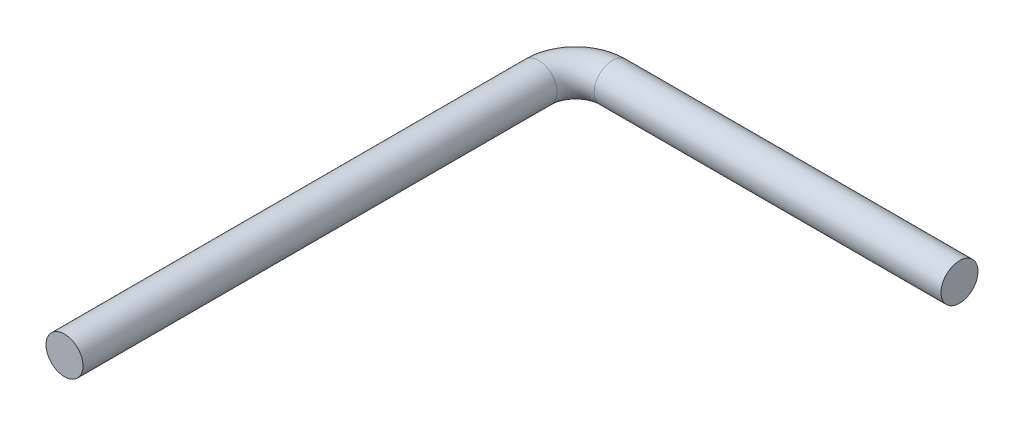
SolidWorks part; units mm, degrees
material "PLA"
ref_plane "Front Plane" through (0, 0, 0) normal (0, 0, 1) x (1, 0, 0)
ref_plane "Top Plane" through (0, 0, 0) normal (0, 1, 0) x (1, 0, 0)
ref_plane "Right Plane" through (0, 0, 0) normal (1, 0, 0) x (0, 0, -1)
sketch "Sketch1" plane through (0, 0, 0) normal (0, 1, 0) x (1, 0, 0)
  line L0 (7.8913, 18.9949) -> (-15.9212, 18.9949)
  line L1 (-18.4612, 16.4549) -> (-18.4612, -16.0876)
  arc A0 (-15.9212, 18.9949) -> (-18.4612, 16.4549) centre (-15.9212, 16.4549) ccw
  point P5 (-18.4612, 18.9949)
  dimension "D3" = 2.54
  dimension "D1" = 23.8125
  dimension "D2" = 32.5425
sketch "Sketch3" plane through (0, 0, 0) normal (1, 0, 0) x (0, 0, -1)
  line L0 (16.4549, 0) -> (-16.0876, 0) construction
  circle A0 centre (18.9949, 0) radius 1.27
  dimension "D1" = 2.54
sweep "Sweep1" add profiles "Sketch3" path "Sketch1"
